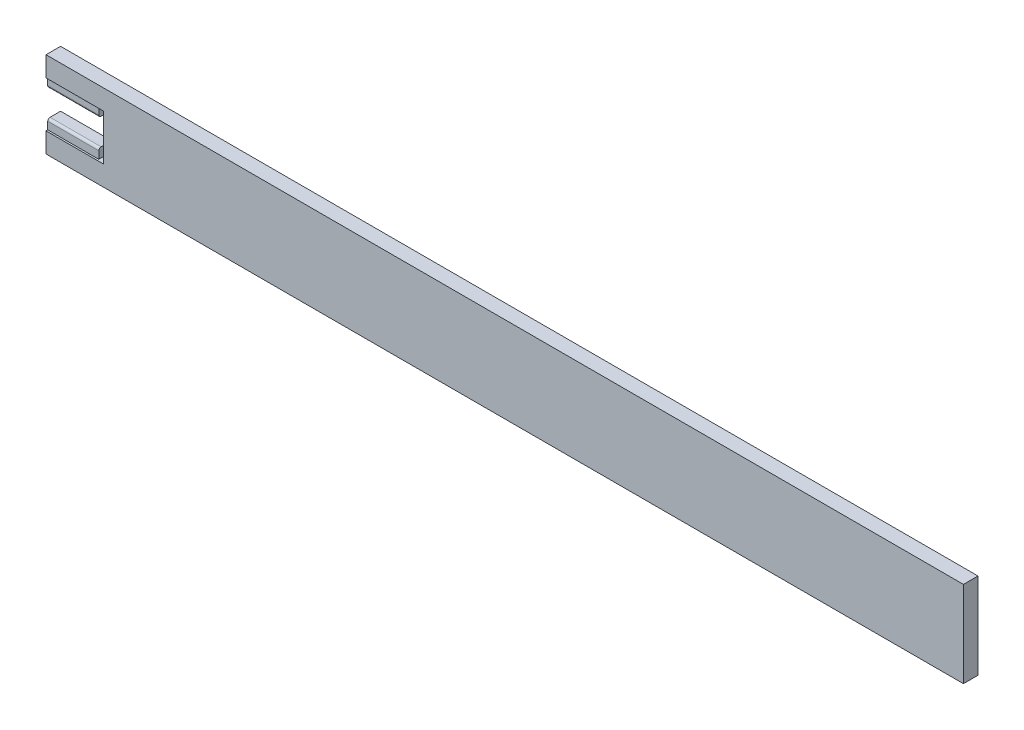
SolidWorks part; units mm, degrees
material "6061 Alloy"
ref_plane "Front Plane" through (0, 0, 0) normal (0, 0, 1) x (1, 0, 0)
ref_plane "Top Plane" through (0, 0, 0) normal (0, 1, 0) x (1, 0, 0)
ref_plane "Right Plane" through (0, 0, 0) normal (1, 0, 0) x (0, 0, -1)
sketch "Sketch1" plane through (0, 0, 0) normal (0, 0, 1) x (1, 0, 0)
  line L1 (0, 0) -> (1600, 0)
  line L2 (0, 0) -> (0, 150)
  line L3 (0, 150) -> (1600, 150)
  line L4 (1600, 0) -> (1600, 150)
  dimension "D1" = 150
  dimension "D2" = 1600
extrude "Boss-Extrude1" add sketch "Sketch1" along normal blind 25.4
sketch "Sketch2" plane through (0, 0, 25.4) normal (0, 0, 1) x (1, 0, 0)
  line L0 (0, 150) -> (0, 0) construction
  line L1 (0, 52) -> (89, 52)
  line L2 (0, 52) -> (0, 98)
  line L3 (0, 98) -> (89, 98)
  line L5 (0, 0) -> (1600, 0) construction
  line L8 (89, 52) -> (89, 35)
  line L9 (89, 115) -> (100, 115)
  line L10 (89, 115) -> (89, 98)
  line L11 (89, 35) -> (100, 35)
  line L12 (100, 115) -> (100, 35)
  dimension "D1" = 100
  dimension "D2" = 46
  dimension "D3" = 52
  dimension "D4" = 80
  dimension "D5" = 17
  dimension "D6" = 11
extrude "Cut-Extrude1" cut sketch "Sketch2" against normal through all
sketch "Sketch3" plane through (0, 0, 25.4) normal (0, 0, 1) x (1, 0, 0)
  line L0 (0, 150) -> (0, 98) construction
  line L1 (0, 115) -> (100, 115)
  line L2 (0, 115) -> (0, 35)
  line L3 (0, 35) -> (100, 35)
  line L4 (100, 115) -> (100, 35)
extrude "Cut-Extrude2" cut sketch "Sketch3" against normal blind 3
fillet "Fillet1" radius 4 2 edges at (44.5, 52, 22.4) (44.5, 98, 22.4)
